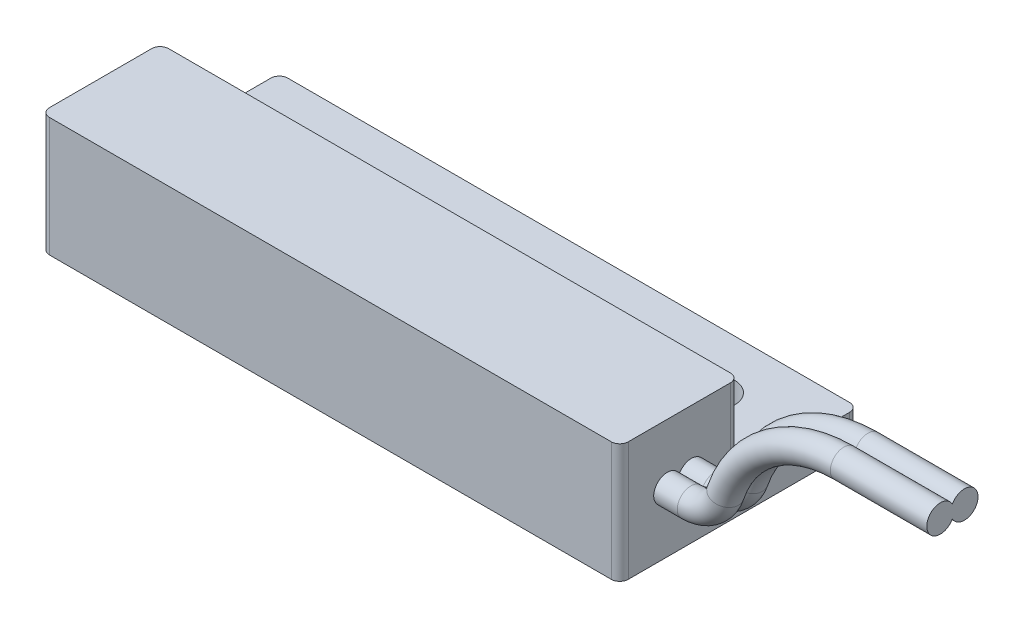
SolidWorks part; units mm, degrees
ref_plane "Front Plane" through (0, 0, 0) normal (0, 0, 1) x (1, 0, 0)
ref_plane "Top Plane" through (0, 0, 0) normal (0, 1, 0) x (1, 0, 0)
ref_plane "Right Plane" through (0, 0, 0) normal (1, 0, 0) x (0, 0, -1)
sketch "Sketch1" plane through (0, 0, 0) normal (0, 1, 0) x (1, 0, 0)
  line L1 (-17, 7) -> (17, 7)
  line L2 (-17, 7) -> (-17, -7)
  line L3 (-17, -7) -> (17, -7)
  line L4 (17, 7) -> (17, -7)
  line L5 (-17, 7) -> (17, -7) construction
  line L6 (-17, -7) -> (17, 7) construction
  point P0 (0, 0)
  dimension "D1" = 34
  dimension "D2" = 14
extrude "Boss-Extrude1" add sketch "Sketch1" along normal blind 2
sketch "Sketch2" plane through (0, 2, 0) normal (0, 1, 0) x (1, 0, 0)
  line L0 (-17, 7) -> (-17, -7) construction
  line L1 (17, -7) -> (-17, -7)
  line L2 (17, -7) -> (17, 0)
  line L3 (17, 0) -> (-17, 0)
  line L4 (-17, -7) -> (-17, 0)
extrude "Boss-Extrude2" add sketch "Sketch2" along normal blind 5
fillet "Fillet1" radius 0.5 6 edges at (17, 3.5, 7) (17, 4.5, 0) (-17, 4.5, 0) (-17, 3.5, 7) (-17, 1, -7) (17, 1, -7)
sketch "Sketch3" plane through (0, 2, 0) normal (0, 1, 0) x (1, 0, 0)
  line L1 (0, 7) -> (0, 0) construction
  line L2 (16.5, 7) -> (-16.5, 7) construction
  line L3 (16.5, 0) -> (-16.5, 0) construction
  circle A0 centre (12, 3.5) radius 1.25
  circle A1 centre (-12, 3.5) radius 1.25
  point P3 (0, 3.5)
  dimension "D1" = 2.5
  dimension "D2" = 12
extrude "Cut-Extrude1" cut sketch "Sketch3" against normal up to next
sketch "Sketch4" plane through (17, 0, 0) normal (1, 0, 0) x (0, 0, -1)
  line L0 (-4.2067, 3.5) -> (-2.7933, 3.5) construction
  line L1 (-3.5, 3.5) -> (-3.5, 7) construction
  line L3 (-6.5, 7) -> (-0.5, 7) construction
  line L4 (-2.7933, 3.5) -> (-7, 3.5) construction
  line L5 (-7, 0) -> (-7, 7) construction
  arc A0 (-3.5, 3.8749) -> (-3.5, 3.1251) centre (-4.2067, 3.5) ccw
  arc A1 (-3.5, 3.1251) -> (-3.5, 3.8749) centre (-2.7933, 3.5) ccw
  dimension "D1" = 1.6
  dimension "D2" = 1.4135
ref_plane "Plane1" through (0, 0, 3.5) normal (0, 0, 1) x (1, 0, 0)
sketch "Sketch5" plane through (0, 0, 3.5) normal (0, 0, 1) x (1, 0, 0)
  line L0 (17, 3.5) -> (18.3826, 3.5)
  line L1 (17, 2.7) -> (17, 4.3) construction
  line L2 (27.3736, 9.9718) -> (33.0382, 9.9718)
  arc A0 (18.3826, 3.5) -> (20.4163, 4.9639) centre (18.3826, 5.6446) ccw
  arc A1 (20.4163, 4.9639) -> (27.3736, 9.9718) centre (27.3736, 2.6351) cw
sweep "Sweep1" add profiles "Sketch4" path "Sketch5"
